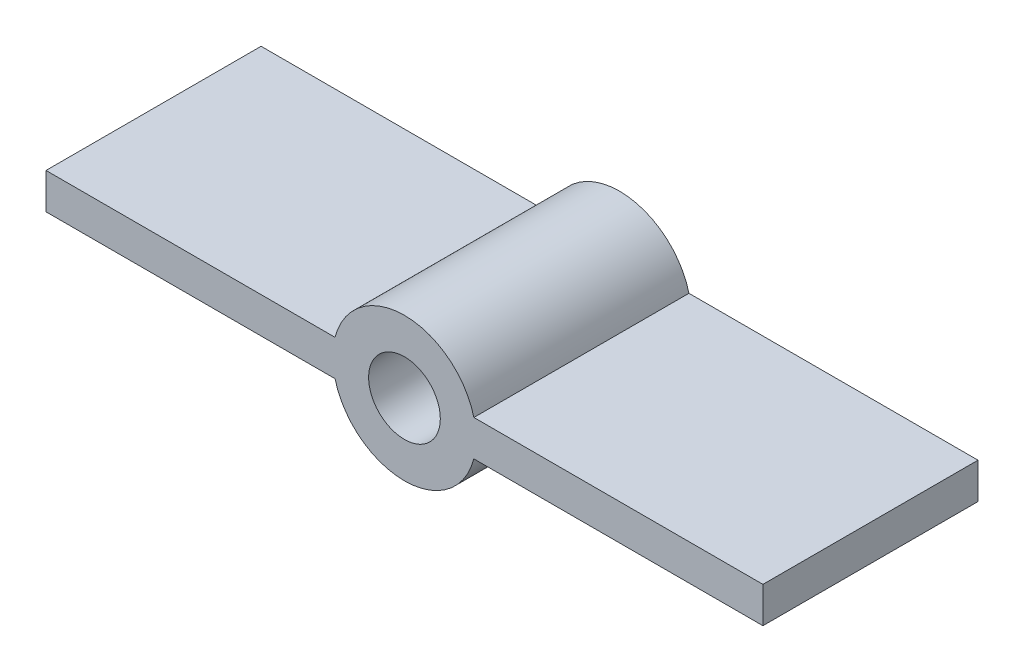
SolidWorks part; units mm, degrees
ref_plane "Front Plane" through (0, 0, 0) normal (0, 0, 1) x (1, 0, 0)
ref_plane "Top Plane" through (0, 0, 0) normal (0, 1, 0) x (1, 0, 0)
ref_plane "Right Plane" through (0, 0, 0) normal (1, 0, 0) x (0, 0, -1)
sketch "Sketch1" plane through (0, 0, 0) normal (0, 1, 0) x (1, 0, 0)
  line L1 (63.5, -19.05) -> (-63.5, -19.05)
  line L2 (63.5, -19.05) -> (63.5, 19.05)
  line L3 (63.5, 19.05) -> (-63.5, 19.05)
  line L4 (-63.5, -19.05) -> (-63.5, 19.05)
  line L5 (63.5, -19.05) -> (-63.5, 19.05) construction
  line L6 (63.5, 19.05) -> (-63.5, -19.05) construction
  point P0 (0, 0)
  dimension "D1" = 38.1
  dimension "D2" = 127
extrude "Boss-Extrude1" add sketch "Sketch1" along normal mid plane 6.35
sketch "Sketch3" plane through (0, 0, 19.05) normal (0, 0, 1) x (1, 0, 0)
  circle A0 centre (0, 0) radius 12.7
  dimension "D1" = 25.4
extrude "Boss-Extrude2" add sketch "Sketch3" against normal up to surface (38.1 mm away) up to face at (0, 0, -19.05)
sketch "Sketch4" plane through (0, 0, 19.05) normal (0, 0, 1) x (1, 0, 0)
  circle A0 centre (0, 0) radius 6.35
  dimension "D1" = 12.7
extrude "Cut-Extrude1" cut sketch "Sketch4" against normal through all
